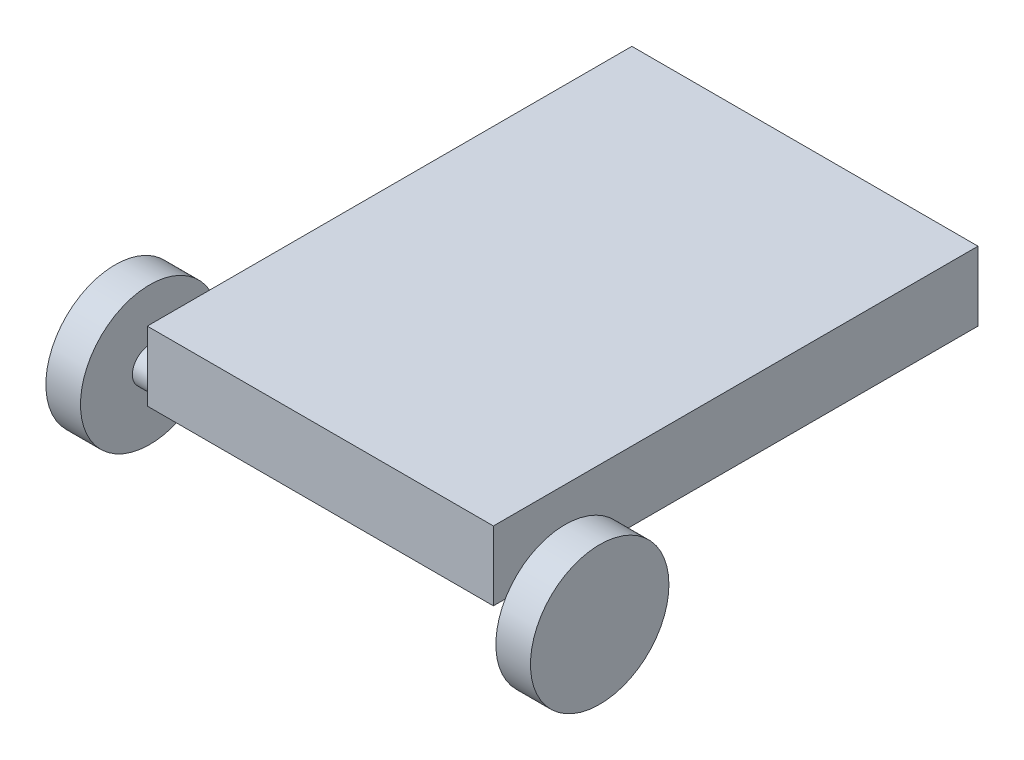
SolidWorks part; units mm, degrees
ref_plane "Alzado" through (0, 0, 0) normal (0, 0, 1) x (1, 0, 0)
ref_plane "Planta" through (0, 0, 0) normal (0, 1, 0) x (1, 0, 0)
ref_plane "Vista lateral" through (0, 0, 0) normal (1, 0, 0) x (0, 0, -1)
sketch "Croquis2" plane through (0, 0, 0) normal (0, 1, 0) x (1, 0, 0)
  line L1 (-25, -35) -> (25, -35)
  line L2 (-25, -35) -> (-25, 35)
  line L3 (-25, 35) -> (25, 35)
  line L4 (25, -35) -> (25, 35)
  line L5 (-25, -35) -> (25, 35) construction
  line L6 (-25, 35) -> (25, -35) construction
  point P0 (0, 0)
  dimension "D1" = 50
  dimension "D2" = 70
extrude "Saliente-Extruir1" add sketch "Croquis2" along normal blind 10
sketch "Croquis4" plane through (0, 0, 0) normal (1, 0, 0) x (0, 0, -1)
  line L0 (27.5, 0) -> (-27.5, 0) construction
  circle A0 centre (-29.6468, 0) radius 2.5
  dimension "D1" = 5
extrude "Saliente-Extruir2" add sketch "Croquis4" along normal blind 30 and the other way blind 30
sketch "Croquis5" plane through (30, 0, 0) normal (1, 0, 0) x (0, 0, -1)
  circle A0 centre (-29.6468, 0) radius 10
  dimension "D1" = 20
extrude "Saliente-Extruir3" add sketch "Croquis5" along normal blind 5
mirror "Simetría1" about plane through (0, 0, 0) normal (1, 0, 0) of "Saliente-Extruir3"
sketch "Croquis6" plane through (0, 0, 0) normal (0, -1, 0) x (1, 0, 0)
  line L0 (0, -11) -> (0, 11) construction
  line L1 (25, -35) -> (-25, -35) construction
  circle A0 centre (0, -30) radius 2.5
  dimension "D1" = 5
  dimension "D2" = 5
extrude "Saliente-Extruir4" add sketch "Croquis6" along normal blind 10
fillet "Redondeo1" radius 2 1 edges at (0, -10, -32.5)
